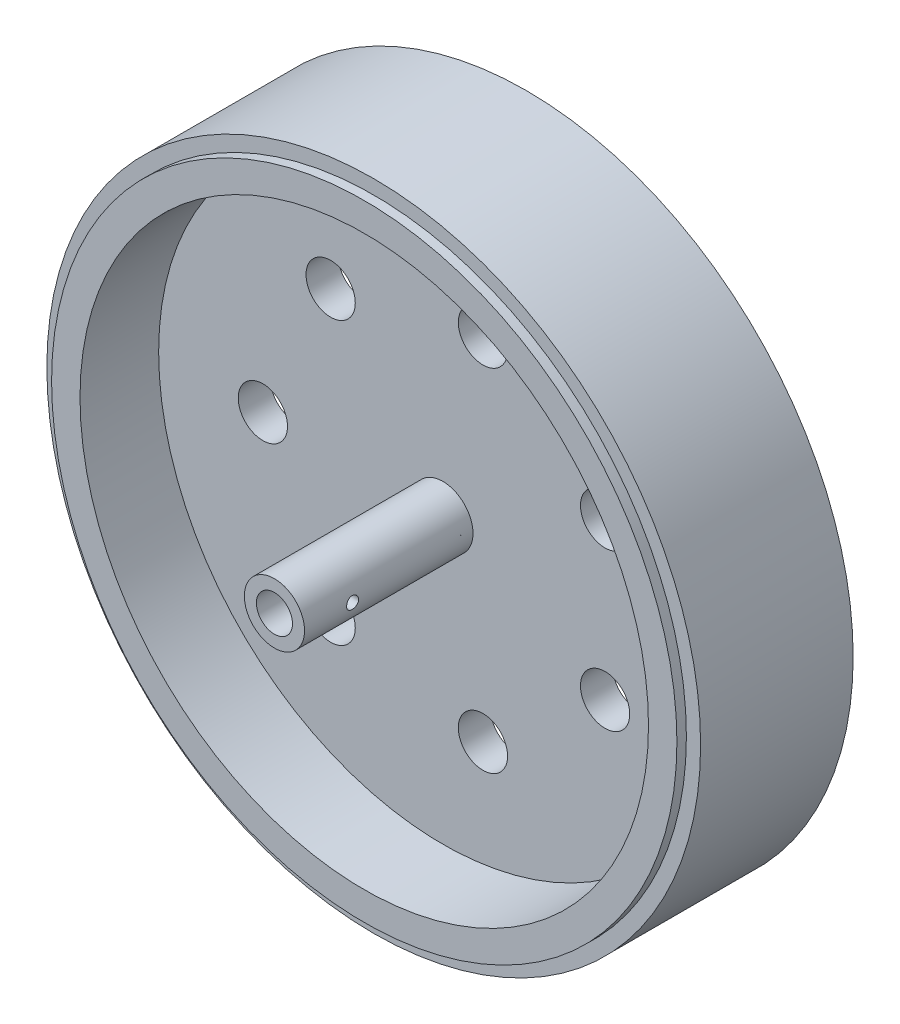
SolidWorks part; units mm, degrees
ref_plane "Front Plane" through (0, 0, 0) normal (0, 0, 1) x (1, 0, 0)
ref_plane "Top Plane" through (0, 0, 0) normal (0, 1, 0) x (1, 0, 0)
ref_plane "Right Plane" through (0, 0, 0) normal (1, 0, 0) x (0, 0, -1)
sketch "Sketch1" plane through (0, 0, 0) normal (0, 0, 1) x (1, 0, 0)
  circle A0 centre (0, 0) radius 30
extrude "Extrude1" add sketch "Sketch1" along normal blind 3.4
sketch "Sketch2" plane through (0, 0, 3.4) normal (0, 0, 1) x (1, 0, 0)
  circle A0 centre (0, 0) radius 30
  circle A1 centre (0, 0) radius 33.4
extrude "Extrude2" add sketch "Sketch2" along normal blind 8.3
sketch "Sketch3" plane through (0, 0, 3.4) normal (0, 0, -1) x (-1, 0, 0)
  circle A0 centre (0, 0) radius 33.4
  circle A1 centre (0, 0) radius 30
extrude "Extrude3" add sketch "Sketch3" along normal blind 9.8
sketch "Sketch4" plane through (0, 0, 11.7) normal (0, 0, 1) x (1, 0, 0)
  circle A0 centre (0, 0) radius 33.4
  circle A1 centre (0, 0) radius 34.5
extrude "Extrude4" add sketch "Sketch4" against normal blind 18.1
sketch "Sketch6" plane through (0, 0, -6.4) normal (0, 0, -1) x (-1, 0, 0)
  circle A0 centre (0, 0) radius 34.5
  circle A1 centre (0, 0) radius 33
extrude "Extrude5" cut sketch "Sketch6" against normal blind 1
sketch "Sketch8" plane through (0, 0, 11.7) normal (0, 0, 1) x (1, 0, 0)
  circle A0 centre (0, 0) radius 0.3756
  circle A1 centre (0, 0) radius 34.5
  circle A2 centre (0, 0) radius 33
extrude "Extrude6" cut sketch "Sketch8" against normal blind 1 contours A2 | A1
sketch "Sketch9" plane through (0, 0, 0) normal (0, 0, -1) x (-1, 0, 0)
  circle A0 centre (0, 0) radius 3.175
  dimension "D1" = 6.35
extrude "Extrude7" add sketch "Sketch9" along normal blind 5.08
sketch "Sketch10" plane through (0, 0, 3.4) normal (0, 0, 1) x (1, 0, 0)
  circle A0 centre (0, 0) radius 3.175
  circle A1 centre (0, 0) radius 1.905
  dimension "D1" = 6.35
  dimension "D2" = 3.81
extrude "Extrude8" add sketch "Sketch10" along normal blind 17.78
sketch "Sketch13" plane through (0, 0, 3.4) normal (0, 0, 1) x (1, 0, 0)
  circle A0 centre (-19, 0) radius 2.6
extrude "Extrude11" cut sketch "Sketch13" against normal blind 10 and the other way blind 10
pattern_circular "CirPattern1" count 7 over 360 about axis through (0, 0, 0) along (0, 0, 1) of "Extrude11"
sketch "Sketch14" plane through (0, 0, 0) normal (1, 0, 0) x (0, 0, -1)
  line L0 (-21.18, 3.175) -> (-21.18, -3.175) construction
  circle A0 centre (-16.1, 0) radius 0.635
  dimension "D1" = 1.27
  dimension "D2" = 5.08
extrude "Cut-Extrude1" cut sketch "Sketch14" along normal up to next
sketch "Sketch15" plane through (0, 0, -5.08) normal (0, 0, -1) x (-1, 0, 0)
  circle A0 centre (0, 0) radius 1.905
  dimension "D1" = 3.81
extrude "Cut-Extrude2" cut sketch "Sketch15" against normal up to next
